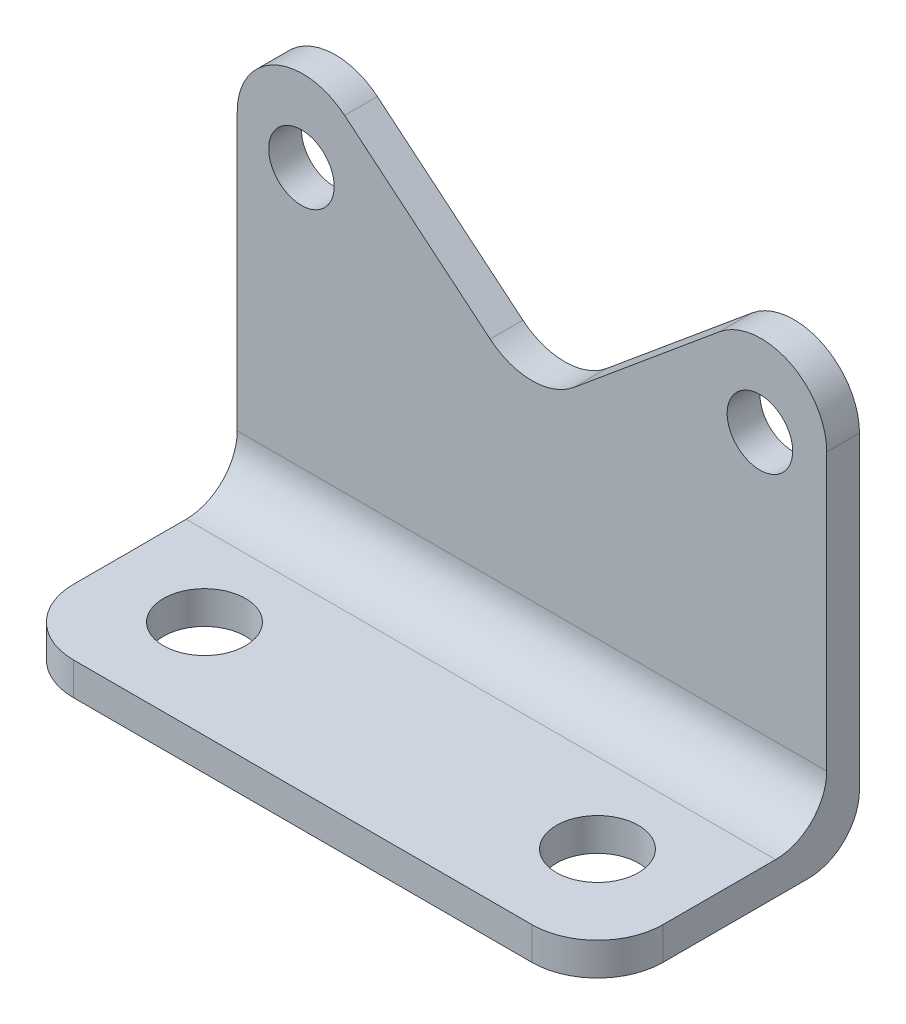
SolidWorks part; units mm, degrees
ref_plane "Front Plane" through (0, 0, 0) normal (0, 0, 1) x (1, 0, 0)
ref_plane "Top Plane" through (0, 0, 0) normal (0, 1, 0) x (1, 0, 0)
ref_plane "Right Plane" through (0, 0, 0) normal (1, 0, 0) x (0, 0, -1)
sketch "Sketch2" plane through (0, 0, 0) normal (0, 0, 1) x (1, 0, 0)
  line L1 (-28.575, 20.6375) -> (28.575, 20.6375)
  line L2 (-28.575, 20.6375) -> (-28.575, -20.6375)
  line L3 (-28.575, -20.6375) -> (28.575, -20.6375)
  line L4 (28.575, 20.6375) -> (28.575, -20.6375)
  line L5 (-28.575, 20.6375) -> (28.575, -20.6375) construction
  line L6 (-28.575, -20.6375) -> (28.575, 20.6375) construction
  point P0 (0, 0)
  dimension "D1" = 57.15
  dimension "D2" = 41.275
extrude "Boss-Extrude1" add sketch "Sketch2" along normal blind 3.175
sketch "Sketch7" plane through (28.575, 0, 0) normal (1, 0, 0) x (0, 0, -1)
  line L0 (0, -20.6375) -> (0, -17.4625)
  line L1 (0, -20.6375) -> (0, 20.6375) construction
  line L2 (0, -17.4625) -> (-25.4, -17.4625)
  line L3 (-25.4, -17.4625) -> (-25.4, -20.6375)
  line L4 (-25.4, -20.6375) -> (0, -20.6375)
  dimension "D1" = 25.4
  dimension "D2" = 3.175
extrude "Boss-Extrude2" add sketch "Sketch7" against normal blind 57.15
sketch "Sketch8" plane through (28.575, 0, 0) normal (1, 0, 0) x (0, 0, -1)
  line L0 (0, -20.6375) -> (0, 20.6375) construction
  line L4 (-25.4, -20.6375) -> (0, -20.6375) construction
  arc A2 (0, -15.6845) -> (-4.953, -20.6375) centre (-4.953, -15.6845) cw
  dimension "D1" = 4.953
extrude "Cut-Extrude3" cut sketch "Sketch8" against normal blind 57.15 and the other way through all
fillet "Fillet1" radius 4.953 1 edges at (0, -17.4625, 3.175)
fillet "Fillet2" radius 6.35 1 edges at (28.575, -19.05, 25.4)
fillet "Fillet3" radius 6.35 1 edges at (-28.575, -19.05, 25.4)
sketch "Sketch13" plane through (0, 0, 3.175) normal (0, 0, 1) x (1, 0, 0)
  line L0 (28.575, -12.5095) -> (28.575, 20.6375) construction
  line L1 (-14.9244, 12.7) -> (12.2774, 12.7) construction
  line L2 (-22.225, -20.6375) -> (22.225, -20.6375) construction
  circle A0 centre (-22.3503, 12.7) radius 3.175
  circle A1 centre (22.0997, 12.7) radius 3.175
  point P9 (0, 0)
  dimension "D1" = 6.35
  dimension "D2" = 6.35
  dimension "D3" = 44.45
  dimension "D4" = 6.4753
  dimension "D5" = 33.3375
extrude "Cut-Extrude5" cut sketch "Sketch13" against normal blind 57.15
sketch "Sketch14" plane through (0, -17.4625, 0) normal (0, 1, 0) x (1, 0, 0)
  line L0 (-28.575, -8.128) -> (-28.575, -19.05) construction
  line L1 (28.575, 0) -> (-28.575, 0) construction
  line L3 (-12.1807, -15.875) -> (9.8148, -15.875) construction
  circle A0 centre (-19.05, -15.875) radius 3.9751
  circle A1 centre (19.05, -15.875) radius 3.9751
  point P11 (-28.575, -13.589)
  dimension "D1" = 7.9502
  dimension "D4" = 7.9502
  dimension "D2" = 15.875
  dimension "D3" = 9.525
  dimension "D5" = 47.625
extrude "Cut-Extrude6" cut sketch "Sketch14" against normal blind 57.15
sketch "Sketch15" plane through (0, 0, 3.175) normal (0, 0, 1) x (1, 0, 0)
  line L0 (-28.575, 20.6375) -> (-28.575, -12.5095) construction
  line L1 (28.575, 20.6375) -> (-28.575, 20.6375) construction
  line L2 (28.575, -12.5095) -> (28.575, 20.6375) construction
  line L3 (-32.5532, 5.9817) -> (35.2635, 5.9817) construction
  line L4 (-22.225, -20.6375) -> (22.225, -20.6375) construction
  line L5 (-18.1666, 19.1714) -> (-4.0584, 7.4478)
  line L6 (-28.575, 14.2875) -> (-28.575, 20.6375)
  line L7 (4.0584, 7.4478) -> (18.1666, 19.1714)
  line L8 (-28.575, 20.6375) -> (-22.225, 20.6375)
  line L9 (22.225, 20.6375) -> (28.575, 20.6375)
  line L10 (28.575, 20.6375) -> (28.575, 14.2875)
  line L11 (-22.225, 20.6375) -> (22.225, 20.6375)
  circle A0 centre (-22.225, 14.2875) radius 6.35
  circle A1 centre (22.225, 14.2875) radius 6.35
  arc A2 (-4.0584, 7.4478) -> (4.0584, 7.4478) centre (0, 12.3317) ccw
  line M8 (-28.575, 20.6375) -> (-28.575, -12.5095)
  line M10 (28.575, -12.5095) -> (28.575, 20.6375)
  line M11 (28.575, 20.6375) -> (-28.575, 20.6375)
  dimension "D1" = 12.7
  dimension "D3" = 12.7
  dimension "D4" = 28.575
  dimension "D2" = 26.6192
extrude "Cut-Extrude8" cut sketch "Sketch15" against normal through all contours L5 A2 L7 A1 A0 M11 | A0 M11 M8 | A1 M10 M11
